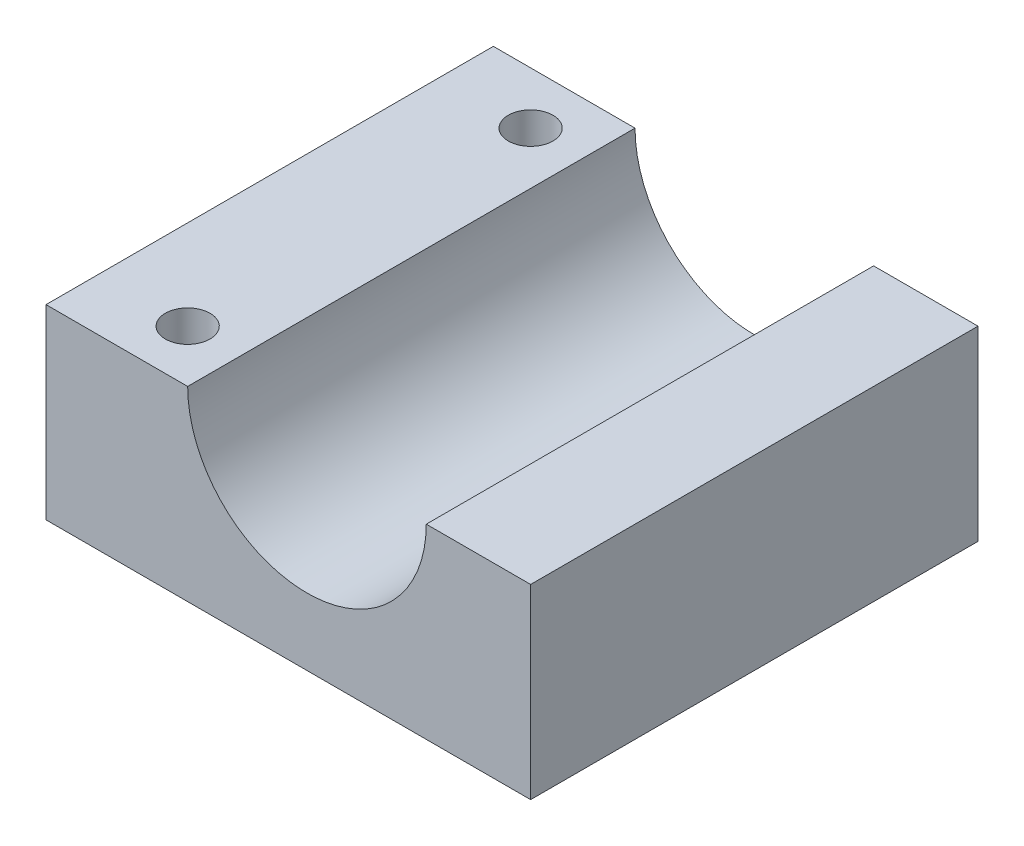
SolidWorks part; units mm, degrees
ref_plane "Front Plane" through (0, 0, 0) normal (0, 0, 1) x (1, 0, 0)
ref_plane "Top Plane" through (0, 0, 0) normal (0, 1, 0) x (1, 0, 0)
ref_plane "Right Plane" through (0, 0, 0) normal (1, 0, 0) x (0, 0, -1)
sketch "Sketch1" plane through (0, 0, 0) normal (0, 0, 1) x (1, 0, 0)
  line L0 (16.0074, 3.6819) -> (23.0074, 3.6819)
  line L1 (-6.9926, 3.6819) -> (0.0074, 3.6819)
  line L2 (-6.9926, 3.6819) -> (-6.9926, -8.8181)
  line L3 (-6.9926, -8.8181) -> (23.0074, -8.8181)
  line L4 (23.0074, 3.6819) -> (23.0074, -8.8181)
  arc A0 (0.0074, 3.6819) -> (16.0074, 3.6819) centre (8.0074, 3.6819) ccw
  dimension "D3" = 16
  dimension "D1" = 12.5
  dimension "D2" = 30
extrude "Boss-Extrude1" add sketch "Sketch1" along normal blind 30
sketch "Sketch2" plane through (0, -8.8181, 0) normal (0, -1, 0) x (1, 0, 0)
  line L0 (-6.9926, 30) -> (23.0074, 30) construction
  line L1 (-6.9926, 30) -> (-6.9926, 0) construction
  line L2 (-6.9926, 0) -> (23.0074, 0) construction
  circle A0 centre (-3.4926, 3.5) radius 1.5
  circle A1 centre (-3.4926, 26.5) radius 1.5
  dimension "D1" = 3
  dimension "D2" = 3
  dimension "D3" = 3.5
  dimension "D4" = 3.5
  dimension "D5" = 3.5
  dimension "D6" = 3.5
extrude "Cut-Extrude1" cut sketch "Sketch2" against normal through all
sketch "Sketch3" plane through (-6.9926, 0, 0) normal (-1, 0, 0) x (0, 0, 1)
  line L1 (0, 3.6819) -> (30, 3.6819)
  line L2 (0, 3.6819) -> (0, -8.8181)
  line L3 (0, -8.8181) -> (30, -8.8181)
  line L4 (30, 3.6819) -> (30, -8.8181)
extrude "Boss-Extrude2" add sketch "Sketch3" along normal blind 2.5
